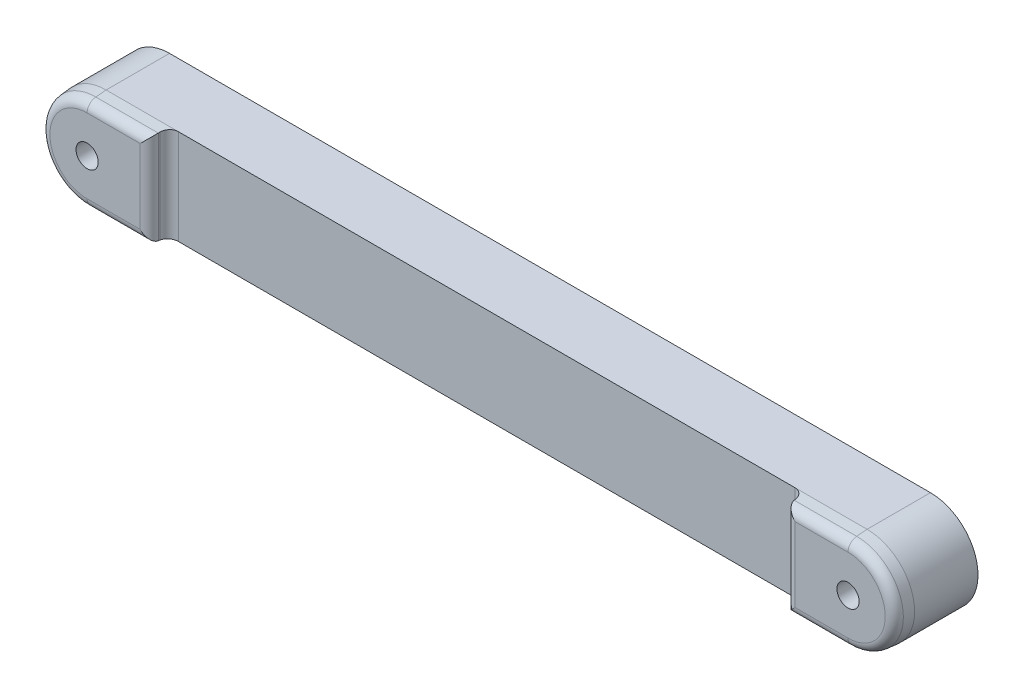
SolidWorks part; units mm, degrees
ref_plane "Front Plane" through (0, 0, 0) normal (0, 0, 1) x (1, 0, 0)
ref_plane "Top Plane" through (0, 0, 0) normal (0, 1, 0) x (1, 0, 0)
ref_plane "Right Plane" through (0, 0, 0) normal (1, 0, 0) x (0, 0, -1)
sketch "Sketch1" plane through (0, 0, 0) normal (0, 0, 1) x (1, 0, 0)
  line L0 (-60, 0) -> (60, 0) construction
  line L1 (-60, 7.5) -> (60, 7.5)
  line L2 (-60, -7.5) -> (60, -7.5)
  arc A0 (-60, 7.5) -> (-60, -7.5) centre (-60, 0) ccw
  arc A1 (60, -7.5) -> (60, 7.5) centre (60, 0) ccw
  point P3 (0, 0)
  point P8 (0, 0)
  point P9 (0, 0)
  dimension "D1" = 120
  dimension "D2" = 15
extrude "Boss-Extrude1" add sketch "Sketch1" along normal blind 10
sketch "Sketch2" plane through (0, 0, 10) normal (0, 0, 1) x (1, 0, 0)
  line L0 (-50, 7.5) -> (-50, -7.5)
  line L2 (-60, -7.5) -> (60, -7.5)
  line L3 (60, 7.5) -> (-60, 7.5)
  line L4 (-60, -7.5) -> (60, -7.5)
  line L5 (60, 7.5) -> (-60, 7.5)
  arc A2 (-60, 7.5) -> (-60, -7.5) centre (-60, 0) ccw
  arc A3 (60, -7.5) -> (60, 7.5) centre (60, 0) ccw
  arc A4 (-60, 7.5) -> (-60, -7.5) centre (-60, 0) ccw
  arc A5 (60, -7.5) -> (60, 7.5) centre (60, 0) ccw
  arc M5 (-60, 7.5) -> (-60, -7.5) centre (-60, 0) ccw
  line M6 (-60, -7.5) -> (60, -7.5)
  line M8 (60, 7.5) -> (-60, 7.5)
  dimension "D2" = 10
  dimension "D1" = 0
extrude "Boss-Extrude2" add sketch "Sketch2" along normal blind 3 draft 5 contours L0 M8 M5 M6
fillet "Fillet1" radius 1.5 5 edges at (-50.2625, 0, 13) (-55.1312, 7.2375, 13) (-67.2375, 0, 13) (-55.1312, -7.2375, 13) (-50, 0, 10)
sketch "Sketch3" plane through (0, 0, 13) normal (0, 0, 1) x (1, 0, 0)
  circle A0 centre (-60, 0) radius 1.75
  dimension "D1" = 3.5
extrude "Cut-Extrude1" cut sketch "Sketch3" against normal through all
sketch "Sketch4" plane through (0, 0, 0) normal (0, 0, -1) x (-1, 0, 0)
  circle A0 centre (60, 0) radius 4
  dimension "D1" = 8
extrude "Cut-Extrude2" cut sketch "Sketch4" against normal blind 10
mirror "Mirror3" about plane through (0, 0, 0) normal (1, 0, 0) of "Fillet1", "Cut-Extrude2", "Cut-Extrude1", "Boss-Extrude2"
chamfer "Chamfer1" distance 2 angle 45 2 edges at (-64, 0, 10) (64, 0, 10)
